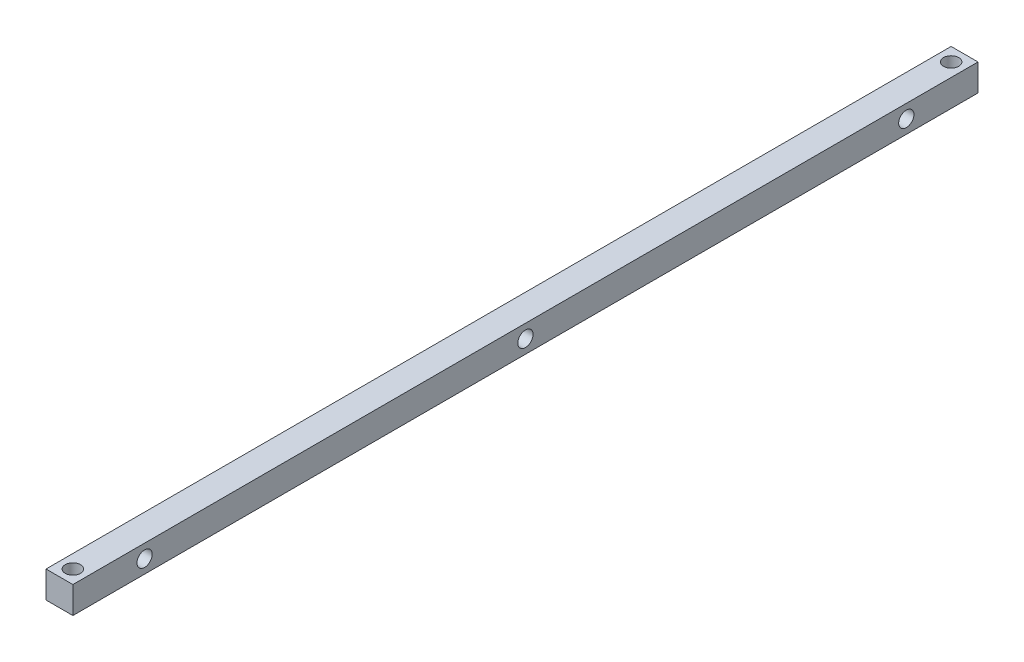
SolidWorks part; units mm, degrees
ref_plane "Ön Düzlem" through (0, 0, 0) normal (0, 0, 1) x (1, 0, 0)
ref_plane "Üst Düzlem" through (0, 0, 0) normal (0, 1, 0) x (1, 0, 0)
ref_plane "Sağ Düzlem" through (0, 0, 0) normal (1, 0, 0) x (0, 0, -1)
sketch "Sketch1" plane through (0, 0, 0) normal (0, 0, 1) x (1, 0, 0)
  line L1 (-7.5, -7.5) -> (7.5, -7.5)
  line L2 (-7.5, -7.5) -> (-7.5, 7.5)
  line L3 (-7.5, 7.5) -> (7.5, 7.5)
  line L4 (7.5, -7.5) -> (7.5, 7.5)
  line L5 (-7.5, -7.5) -> (7.5, 7.5) construction
  line L6 (-7.5, 7.5) -> (7.5, -7.5) construction
  point P0 (0, 0)
  dimension "D1" = 15
extrude "Boss-Extrude1" add sketch "Sketch1" along normal mid plane 505
hole_wizard "Hole2" positions "Sketch7" profile "Sketch8" legacy
sketch "Sketch7" plane through (0, -7.5, 0) normal (0, -1, 0) x (-1, 0, 0)
  line L0 (7.5, 252.5) -> (-7.5, 252.5) construction
  point P0 (0, 245)
  dimension "D1" = 7.5
sketch "Sketch8" plane through (0, -7.5, -245) normal (1, 0, 0) x (0, 0, -1)
  line L0 (0, 0) -> (0, 15)
  line L1 (0, 15) -> (4.25, 15)
  line L2 (4.25, 15) -> (4.25, 8)
  line L3 (4.25, 8) -> (7, 8)
  line L4 (7, 8) -> (7, 0)
  line L5 (7, 0) -> (0, 0)
  line L6 (0, 110) -> (0, -10) construction
  dimension "Diameter" = 8.5
  dimension "Depth" = 15
  dimension "C-Bore Diameter" = 14
  dimension "C-Bore Depth" = 8
mirror "Mirror1" about plane through (0, 0, 0) normal (0, 0, 1) of "Hole2"
hole_wizard "Hole3" positions "Sketch9" profile "Sketch10" legacy
sketch "Sketch9" plane through (-7.5, 0, 0) normal (-1, 0, 0) x (0, 0, 1)
  line L0 (-252.5, 7.5) -> (-252.5, -7.5) construction
  point P0 (-212.5, 0)
  point P3 (0, 0)
  dimension "D1" = 40
sketch "Sketch10" plane through (-7.5, 0, -212.5) normal (0, 1, 0) x (0, 0, 1)
  line L0 (0, 0) -> (0, 15)
  line L1 (0, 15) -> (4.25, 15)
  line L2 (4.25, 15) -> (4.25, 8)
  line L3 (4.25, 8) -> (7, 8)
  line L4 (7, 8) -> (7, 0)
  line L5 (7, 0) -> (0, 0)
  line L6 (0, 110) -> (0, -10) construction
  dimension "Diameter" = 8.5
  dimension "Depth" = 15
  dimension "C-Bore Diameter" = 14
  dimension "C-Bore Depth" = 8
pattern_linear "LPattern1" count 3 spacing 212.5 along (0, 0, 1) of "Hole3"
